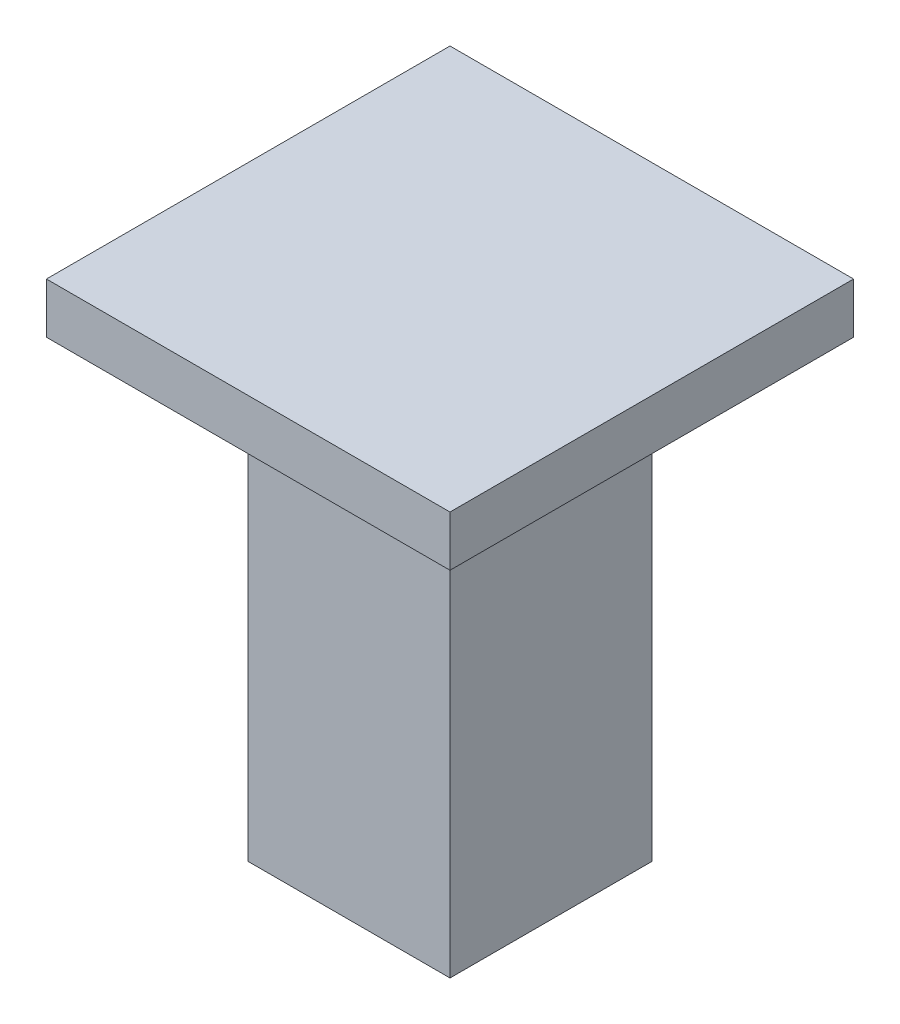
SolidWorks part; units mm, degrees
ref_plane "Front Plane" through (0, 0, 0) normal (0, 0, 1) x (1, 0, 0)
ref_plane "Top Plane" through (0, 0, 0) normal (0, 1, 0) x (1, 0, 0)
ref_plane "Right Plane" through (0, 0, 0) normal (1, 0, 0) x (0, 0, -1)
sketch "Sketch1" plane through (0, 0, 0) normal (0, 1, 0) x (1, 0, 0)
  line L1 (0, 0) -> (20, 0)
  line L2 (0, 0) -> (0, -20)
  line L3 (0, -20) -> (20, -20)
  line L4 (20, 0) -> (20, -20)
  dimension "D1" = 20
  dimension "D2" = 20
extrude "Boss-Extrude1" add sketch "Sketch1" along normal blind 50
sketch "Sketch2" plane through (0, 50, 0) normal (0, 1, 0) x (1, 0, 0)
  line L0 (10, 0) -> (10, -20) construction
  line L1 (20, 0) -> (0, 0) construction
  line L2 (0, -20) -> (20, -20) construction
  line L3 (0, -10) -> (20, -10) construction
  line L4 (0, 0) -> (0, -20) construction
  line L5 (20, -20) -> (20, 0) construction
  line L7 (-10, 10) -> (30, 10)
  line L8 (-10, 10) -> (-10, -30)
  line L9 (-10, -30) -> (30, -30)
  line L10 (30, 10) -> (30, -30)
  dimension "D1" = 20
  dimension "D2" = 20
  dimension "D3" = 20
  dimension "D4" = 20
extrude "Boss-Extrude2" add sketch "Sketch2" against normal blind 5
